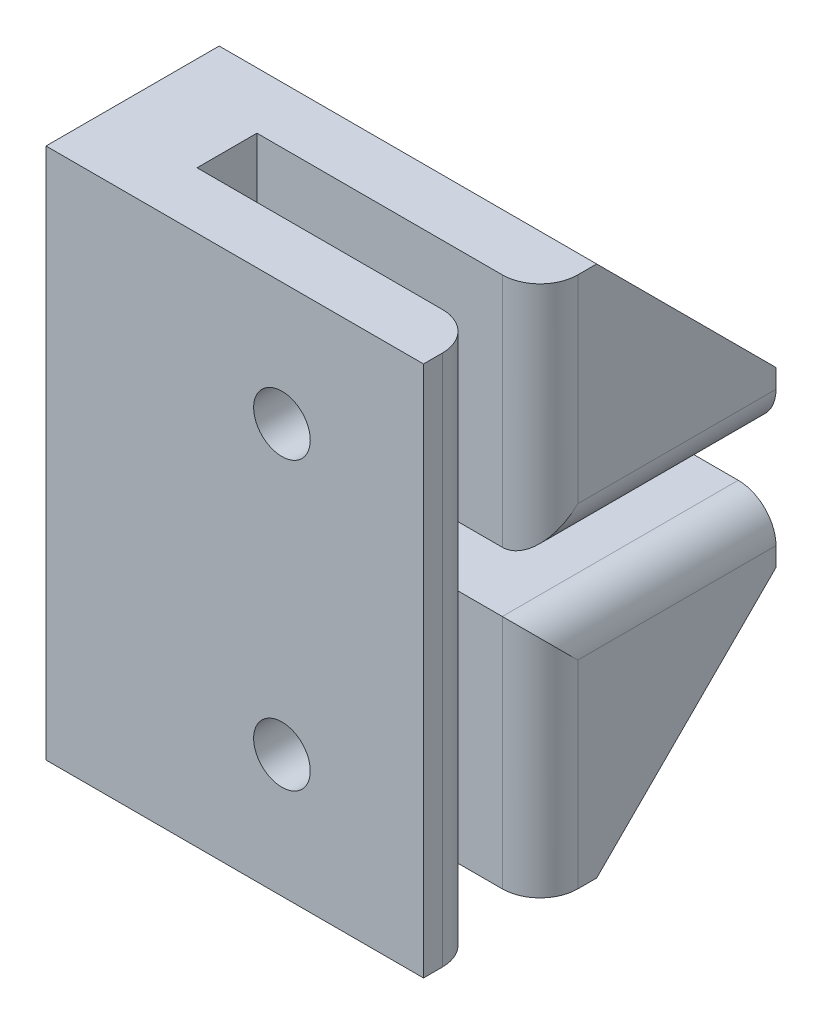
SolidWorks part; units mm, degrees
ref_plane "Front Plane" through (0, 0, 0) normal (0, 0, 1) x (1, 0, 0)
ref_plane "Top Plane" through (0, 0, 0) normal (0, 1, 0) x (1, 0, 0)
ref_plane "Right Plane" through (0, 0, 0) normal (1, 0, 0) x (0, 0, -1)
sketch "Sketch1" plane through (0, 0, 0) normal (1, 0, 0) x (0, 0, -1)
  line L0 (0, 0) -> (0, -12.5) construction
  line L1 (0, -12.5) -> (-3.175, -12.5)
  line L2 (-3.175, -12.5) -> (-3.175, 3.175) construction
  line L3 (-3.175, 3.175) -> (12.5, 3.175) construction
  line L4 (12.5, 3.175) -> (12.5, 0)
  line L5 (12.5, 0) -> (0, 0) construction
  line L6 (0, -12.5) -> (3, -12.5)
  line L7 (3, -12.5) -> (12.5, -3)
  line L8 (12.5, -3) -> (12.5, 0)
  line L9 (12.5, 3.175) -> (12.5, 6.175)
  line L11 (-6.175, 15.675) -> (-6.175, -12.5)
  line L12 (-6.175, -12.5) -> (-3.175, -12.5)
  line L13 (-3.175, 3.175) -> (-3.175, 15.675) construction
  line L14 (-3.175, 15.675) -> (0, 15.675)
  line L15 (0, 15.675) -> (0, 3.175) construction
  line L16 (-6.175, 15.675) -> (-3.175, 15.675)
  line L17 (0, 15.675) -> (3, 15.675)
  line L18 (3, 15.675) -> (12.5, 6.175)
  dimension "D1" = 3.175
  dimension "D2" = 3.175
  dimension "D3" = 12.5
  dimension "D4" = 12.5
  dimension "D5" = 3
  dimension "D6" = 3
  dimension "D7" = 3
  dimension "D8" = 3
  dimension "D9" = 12.5
  dimension "D10" = 3
extrude "Boss-Extrude1" add sketch "Sketch1" along normal blind 20
sketch "Sketch2" plane through (20, 0, 0) normal (1, 0, 0) x (0, 0, -1)
  line L0 (-3.175, -12.5) -> (0, -12.5)
  line L1 (0, -12.5) -> (0, 0)
  line L2 (0, 0) -> (12.5, 0)
  line L3 (12.5, 0) -> (12.5, 3.175)
  line L4 (12.5, 3.175) -> (0, 3.175)
  line L5 (-3.175, 3.175) -> (-3.175, -12.5)
  line L6 (-3.175, 3.175) -> (-3.175, 15.675)
  line L7 (3, 15.675) -> (-6.175, 15.675) construction
  line L8 (-3.175, 15.675) -> (0, 15.675)
  line L9 (0, 15.675) -> (0, 3.175)
extrude "Cut-Extrude1" cut sketch "Sketch2" against normal blind 15
fillet "Fillet1" radius 2 5 edges at (20, 1.5875, 3.175) (20, -6.25, 0) (20, 0, -6.25) (20, 3.175, -6.25) (20, 9.425, 0)
sketch "Sketch5" plane through (0, 0, 6.175) normal (0, 0, 1) x (1, 0, 0)
  line L0 (5, 15.675) -> (5, -12.5) construction
  line L1 (20, 15.675) -> (0, 15.675) construction
  line L2 (20, -12.5) -> (0, -12.5) construction
  line L3 (0, 15.675) -> (0, -12.5) construction
  line L4 (5, 9.175) -> (20, 9.175) construction
  line L5 (20, 15.675) -> (20, -12.5) construction
  line L6 (5, -6) -> (20, -6) construction
  line L7 (5, 3.175) -> (18, 3.175) construction
  line L8 (5, 0) -> (18, 0) construction
  circle A0 centre (12.5, 9.175) radius 1.5
  circle A1 centre (12.5, -6) radius 1.5
  dimension "D4" = 3
  dimension "D5" = 3
  dimension "D1" = 5
  dimension "D2" = 6
  dimension "D3" = 6
extrude "Cut-Extrude4" cut sketch "Sketch5" against normal through all
scale "Scale1" scale about centroid uniform scaling yes scale factor 1.02
